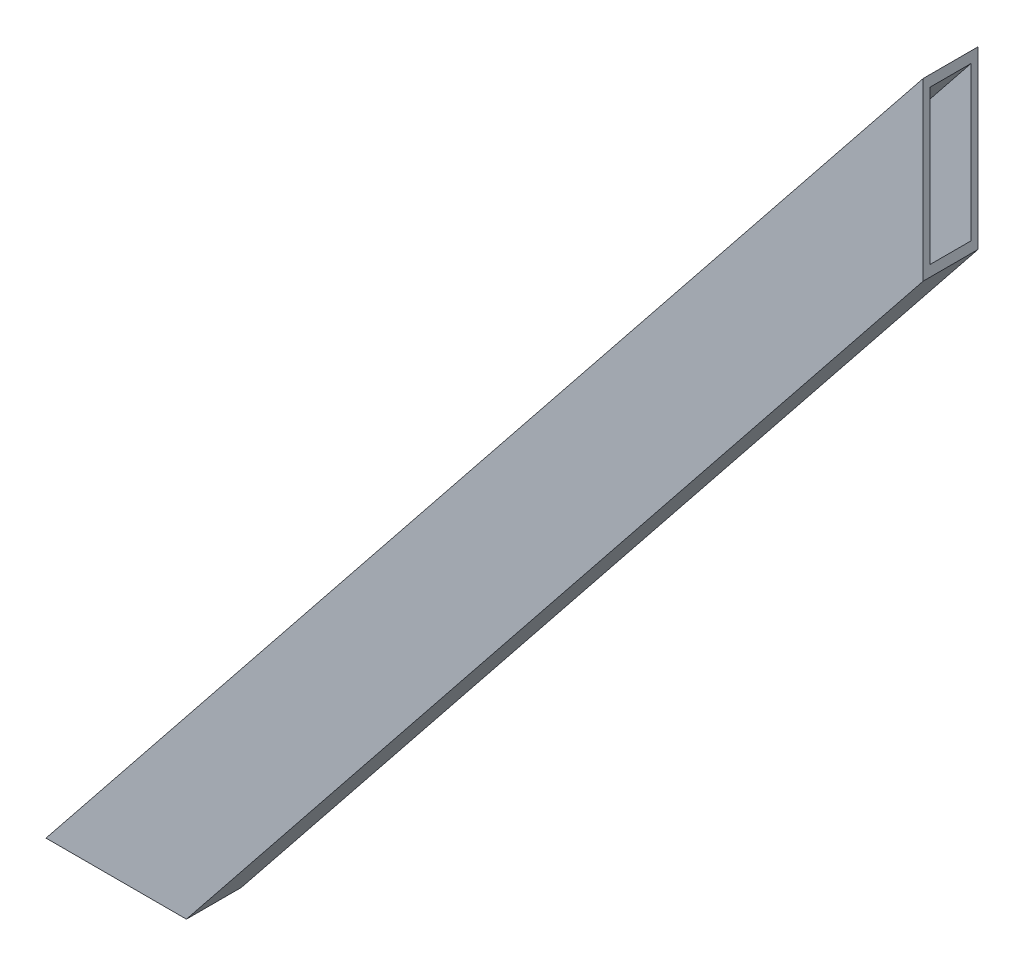
SolidWorks part; units mm, degrees
material "6063-T1"
ref_plane "Front Plane" through (0, 0, 0) normal (0, 0, 1) x (1, 0, 0)
ref_plane "Top Plane" through (0, 0, 0) normal (0, 1, 0) x (1, 0, 0)
ref_plane "Right Plane" through (0, 0, 0) normal (1, 0, 0) x (0, 0, -1)
sketch "Sketch1" plane through (0, 0, 0) normal (0, 0, 1) x (1, 0, 0)
  line L0 (0, 0) -> (406.4, 508)
  line L1 (406.4, 508) -> (406.4, 426.6803)
  line L2 (406.4, 426.6803) -> (65.0557, 0)
  line L3 (65.0557, 0) -> (0, 0)
  dimension "D1" = 406.4
  dimension "D2" = 508
  dimension "D3" = 50.8
extrude "Boss-Extrude1" add sketch "Sketch1" along normal blind 25.4
shell "Shell1" thickness 3.175
sketch "Sketch2" plane through (0, 0, 25.4) normal (0, 0, 1) x (1, 0, 0)
  line L0 (90.7409, 49.3868) -> (344.6169, 366.7319)
  line L1 (90.7409, 49.3868) -> (67.9317, 67.6342)
  line L2 (344.6169, 366.7319) -> (321.8077, 384.9793)
  line L3 (67.9317, 67.6342) -> (321.8077, 384.9793)
  line L4 (406.4, 508) -> (0, 0) construction
  line L5 (65.0557, 0) -> (406.4, 426.6803) construction
  line L6 (79.3363, 58.5105) -> (333.2123, 375.8556) construction
  line L7 (194.8697, 226.3067) -> (217.6789, 208.0594) construction
  line L8 (186.4402, 233.0503) -> (226.1084, 201.3158) construction
  circle A0 centre (68.4275, 75.3695) radius 2.3813
  circle A1 centre (116.0293, 134.8717) radius 2.3813
  circle A2 centre (163.6311, 194.3739) radius 2.3812
  circle A3 centre (193.3822, 170.573) radius 2.3812
  circle A4 centre (145.7804, 111.0708) radius 2.3813
  circle A5 centre (98.1786, 51.5686) radius 2.3813
  circle A6 centre (344.1211, 358.9966) radius 2.3813
  circle A7 centre (296.5193, 299.4944) radius 2.3813
  circle A8 centre (248.9176, 239.9922) radius 2.3812
  circle A9 centre (219.1664, 263.7931) radius 2.3812
  circle A10 centre (266.7682, 323.2953) radius 2.3813
  circle A11 centre (314.37, 382.7975) radius 2.3813
  circle A12 centre (191.3988, 229.0835) radius 2.3813
  circle A13 centre (221.1499, 205.2826) radius 2.3813
  dimension "D5" = 4.7625
  dimension "D9" = 4.7625
  dimension "D10" = 4.7625
  dimension "D1" = 406.4
  dimension "D2" = 29.21
  dimension "D3" = 10.795
  dimension "D4" = 57.15
  dimension "D6" = 6.35
  dimension "D7" = 6.35
  dimension "D11" = 6.35
  dimension "D12" = 6.35
  dimension "D8" = 3
extrude "Cut-Extrude1" cut sketch "Sketch2" against normal through all from offset 7.62 offset against normal yes
fillet "Fillet1" radius 3.175 4 edges at (321.8077, 384.9793, 1.5875) (344.6169, 366.7319, 1.5875) (90.7409, 49.3868, 1.5875) (67.9317, 67.6342, 1.5875)
